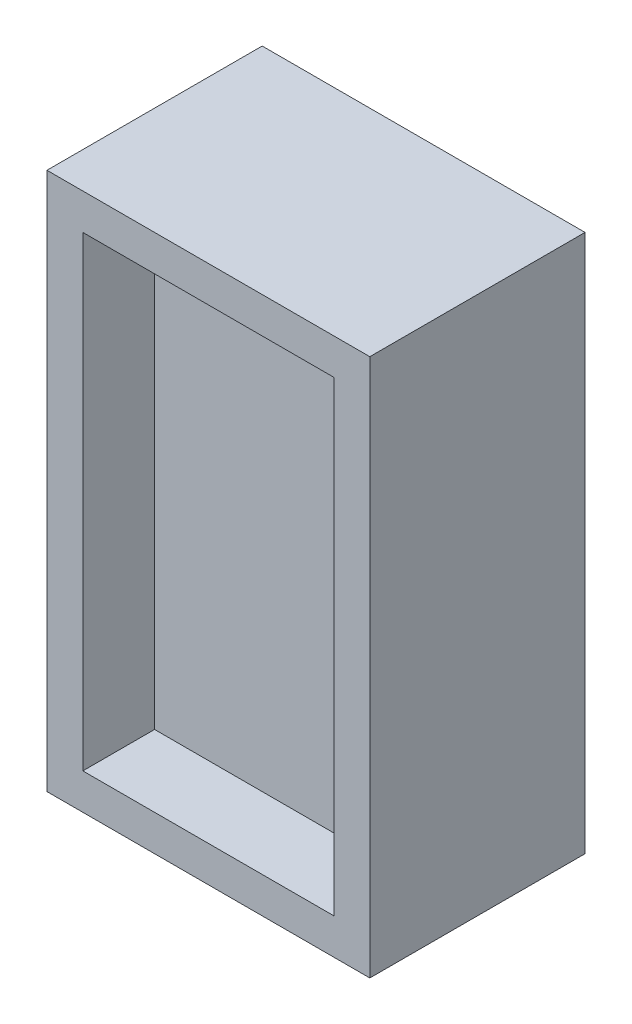
SolidWorks part; units mm, degrees
ref_plane "Front Plane" through (0, 0, 0) normal (0, 0, 1) x (1, 0, 0)
ref_plane "Top Plane" through (0, 0, 0) normal (0, 1, 0) x (1, 0, 0)
ref_plane "Right Plane" through (0, 0, 0) normal (1, 0, 0) x (0, 0, -1)
sketch "Sketch1" plane through (0, 0, 0) normal (0, 0, 1) x (1, 0, 0)
  line L1 (0, 0) -> (57.15, 0)
  line L2 (0, 0) -> (0, -95.25)
  line L3 (0, -95.25) -> (57.15, -95.25)
  line L4 (57.15, 0) -> (57.15, -95.25)
extrude "Boss-Extrude1" add sketch "Sketch1" along normal blind 38.1
sketch "Sketch2" plane through (0, 0, 38.1) normal (0, 0, 1) x (1, 0, 0)
  line L0 (57.15, 0) -> (0, 0) construction
  line L1 (6.35, -6.35) -> (50.8, -6.35)
  line L2 (6.35, -6.35) -> (6.35, -88.9)
  line L3 (6.35, -88.9) -> (50.8, -88.9)
  line L4 (50.8, -6.35) -> (50.8, -88.9)
  line L5 (0, -95.25) -> (57.15, -95.25) construction
  line L6 (57.15, -95.25) -> (57.15, 0) construction
  line L7 (0, 0) -> (0, -95.25) construction
  dimension "D1" = 6.35
  dimension "D2" = 6.35
  dimension "D3" = 6.35
  dimension "D4" = 6.35
extrude "Cut-Extrude1" cut sketch "Sketch2" against normal blind 12.7
